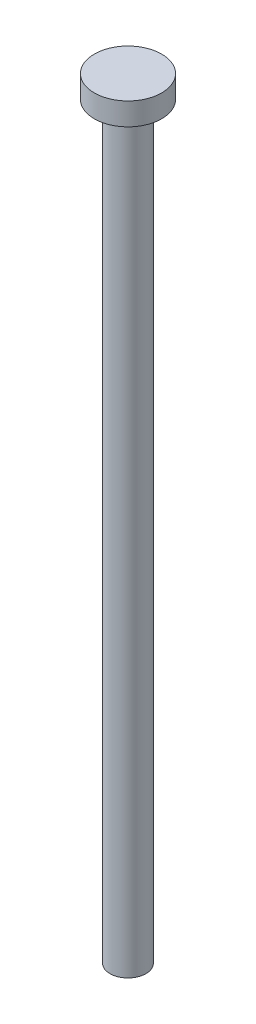
SolidWorks part; units mm, degrees
material "AISI 1020"
ref_plane "Alzado" through (0, 0, 0) normal (0, 0, 1) x (1, 0, 0)
ref_plane "Planta" through (0, 0, 0) normal (0, 1, 0) x (1, 0, 0)
ref_plane "Vista lateral" through (0, 0, 0) normal (1, 0, 0) x (0, 0, -1)
sketch "Croquis1" plane through (0, 0, 0) normal (0, 1, 0) x (1, 0, 0)
  circle A0 centre (0, 0) radius 2.4
  dimension "D1" = 4.8
extrude "Saliente-Extruir1" add sketch "Croquis1" along normal mid plane 100
sketch "Croquis2" plane through (0, 50, 0) normal (0, 1, 0) x (1, 0, 0)
  circle A0 centre (0, 0) radius 4.5
  dimension "D1" = 9
extrude "Saliente-Extruir2" add sketch "Croquis2" along normal blind 3
